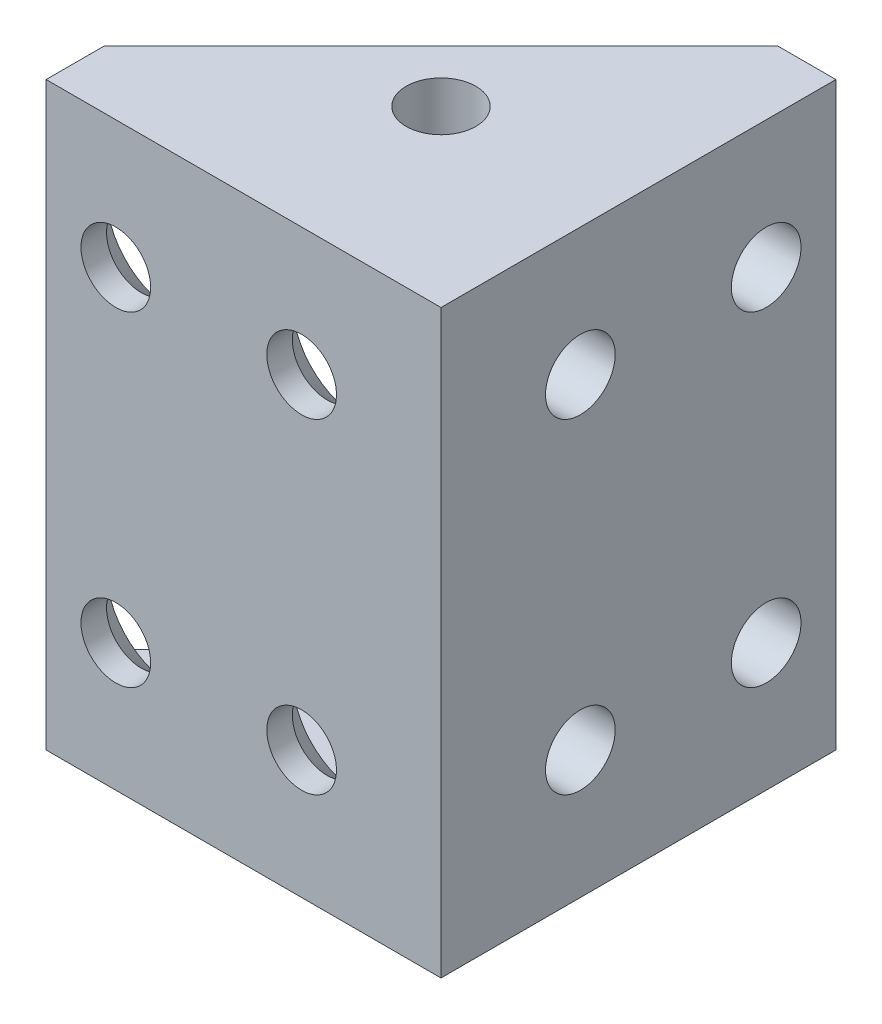
SolidWorks part; units mm, degrees
material "6061-T6 (SS)"
ref_plane "前视基准面" through (0, 0, 0) normal (0, 0, 1) x (1, 0, 0)
ref_plane "上视基准面" through (0, 0, 0) normal (0, 1, 0) x (1, 0, 0)
ref_plane "右视基准面" through (0, 0, 0) normal (1, 0, 0) x (0, 0, -1)
sketch "草图1" plane through (0, 0, 0) normal (0, 1, 0) x (1, 0, 0)
  line L0 (6, 1.25) -> (6, 15.75)
  line L1 (8.5, -1.25) -> (-8.5, -1.25)
  line L2 (8.5, -1.25) -> (8.5, 1.25)
  line L3 (8.5, 1.25) -> (-8.5, 1.25) construction
  line L4 (-8.5, -1.25) -> (-8.5, 1.25)
  line L5 (8.5, -1.25) -> (-8.5, 1.25) construction
  line L6 (8.5, 1.25) -> (-8.5, -1.25) construction
  line L7 (6, 15.75) -> (8.5, 15.75)
  line L8 (8.5, 15.75) -> (8.5, 1.25)
  line L9 (-8.5, 1.25) -> (6, 1.25)
  point P0 (0, 0)
  dimension "D1" = 2.5
  dimension "D2" = 17
  dimension "D3" = 17
extrude "凸台-拉伸1" add sketch "草图1" along normal blind 25
sketch "草图5" plane through (0, 0, 0) normal (0, -1, 0) x (1, 0, 0)
  line L0 (6, -15.75) -> (6, -1.25)
  line L1 (6, -1.25) -> (-8.5, -1.25)
  line L2 (-8.5, -1.25) -> (6, -15.75)
extrude "凸台-拉伸3" add sketch "草图5" against normal blind 2.5
sketch "草图6" plane through (0, 25, 0) normal (0, 1, 0) x (1, 0, 0)
  line L0 (6, 15.75) -> (6, 1.25)
  line L1 (6, 1.25) -> (-8.5, 1.25)
  line L2 (-8.5, 1.25) -> (6, 15.75)
extrude "凸台-拉伸4" add sketch "草图6" against normal blind 2.5
sketch "草图8" plane through (0, 0, -1.25) normal (0, 0, -1) x (-1, 0, 0)
  line L0 (-6, 12.5) -> (1.5, 12.5) construction
  line L1 (-6, 22.5) -> (-6, 2.5) construction
  line L2 (1.5, 17.5) -> (1.5, 12.5) construction
  line L3 (5.5, 19.5) -> (-2.5, 19.5) construction
  line L4 (5.5, 19.5) -> (5.5, 5.5) construction
  line L5 (5.5, 5.5) -> (-2.5, 5.5) construction
  line L6 (-2.5, 19.5) -> (-2.5, 5.5) construction
  line L7 (5.5, 19.5) -> (-2.5, 5.5) construction
  line L8 (5.5, 5.5) -> (-2.5, 19.5) construction
  line L11 (8.5, 22.5) -> (8.5, 2.5) construction
  circle A0 centre (-2.5, 19.5) radius 1.5
  circle A1 centre (5.5, 19.5) radius 1.5
  circle A2 centre (5.5, 5.5) radius 1.5
  circle A3 centre (-2.5, 5.5) radius 1.5
  circle A4 centre (5.5, 5.5) radius 2.75 construction
  circle A5 centre (-2.5, 5.5) radius 2.75 construction
  dimension "D1" = 3
  dimension "D4" = 5.5
  dimension "D6" = 5.5
  dimension "D2" = 14
  dimension "D3" = 8
  dimension "D5" = 3
extrude "切除-拉伸1" cut sketch "草图8" against normal through all
sketch "草图9" plane through (6, 0, 0) normal (-1, 0, 0) x (0, 0, 1)
  line L0 (-8.75, 12.5) -> (-1.25, 12.5) construction
  line L1 (-4.75, 19.5) -> (-12.75, 19.5) construction
  line L2 (-4.75, 19.5) -> (-4.75, 5.5) construction
  line L3 (-4.75, 5.5) -> (-12.75, 5.5) construction
  line L4 (-12.75, 19.5) -> (-12.75, 5.5) construction
  line L5 (-4.75, 19.5) -> (-12.75, 5.5) construction
  line L6 (-4.75, 5.5) -> (-12.75, 19.5) construction
  line L7 (-1.25, 22.5) -> (-1.25, 2.5) construction
  line L8 (-8.75, 12.5) -> (-8.75, 17.5) construction
  line L10 (-15.75, 22.5) -> (-15.75, 2.5) construction
  circle A0 centre (-12.75, 19.5) radius 1.5
  circle A1 centre (-12.75, 5.5) radius 1.5
  circle A2 centre (-4.75, 19.5) radius 1.5
  circle A3 centre (-4.75, 5.5) radius 1.5
  circle A4 centre (-12.75, 19.5) radius 2.75 construction
  point P0 (-8.75, 12.5)
  dimension "D3" = 3
  dimension "D5" = 5.5
  dimension "D1" = 14
  dimension "D2" = 8
  dimension "D4" = 3
extrude "切除-拉伸2" cut sketch "草图9" against normal through all
sketch "草图10" plane through (0, 0, 0) normal (0, -1, 0) x (1, 0, 0)
  line L0 (8.5, 1.25) -> (8.5, -15.75) construction
  line L1 (-8.5, 1.25) -> (8.5, 1.25) construction
  circle A0 centre (1, -6.25) radius 1.5
  dimension "D3" = 3
  dimension "D1" = 7.5
  dimension "D2" = 7.5
extrude "切除-拉伸3" cut sketch "草图10" against normal through all
hole_wizard "打孔尺寸(%根据十字)槽沉头木螺钉的类型2" positions "3D草图3" profile "草图14" countersink size "M3" standard "GB" end condition through all
sketch3d "3D草图3"
  line L0 (-5.5, 5.5, 1.25) -> (-5.5, 5.5, -1.25) construction
  line L1 (2.5, 5.5, 1.25) -> (2.5, 5.5, -1.25) construction
  line L2 (2.5, 19.5, 1.25) -> (2.5, 19.5, -1.25) construction
  line L3 (-5.5, 19.5, 1.25) -> (-5.5, 19.5, -1.25) construction
  point P0 (-5.5, 5.5, -1.25)
  point P4 (2.5, 5.5, -1.25)
  point P8 (2.5, 19.5, -1.25)
  point P12 (-5.5, 19.5, -1.25)
sketch "草图14" plane through (-5.5, 5.5, -1.25) normal (1, 0, 0) x (0, 1, 0)
  line L0 (0, 0) -> (0, 2.5)
  line L1 (0, 2.5) -> (1.5, 2.5)
  line L2 (1.5, 2.5) -> (1.5, 1.4)
  line L3 (1.5, 1.4) -> (2.9, 0)
  line L5 (2.9, 0) -> (0, 0)
  line L6 (-1.5, 1.4) -> (-2.9, 0) construction
  line L11 (0, -6.35) -> (0, 107.95) construction
  dimension "通孔孔直径" = 3
  dimension "通孔孔深度" = 2.5
  dimension "近端锥形沉头孔直径" = 5.8
  dimension "近端锥形沉头孔角度" = 90
